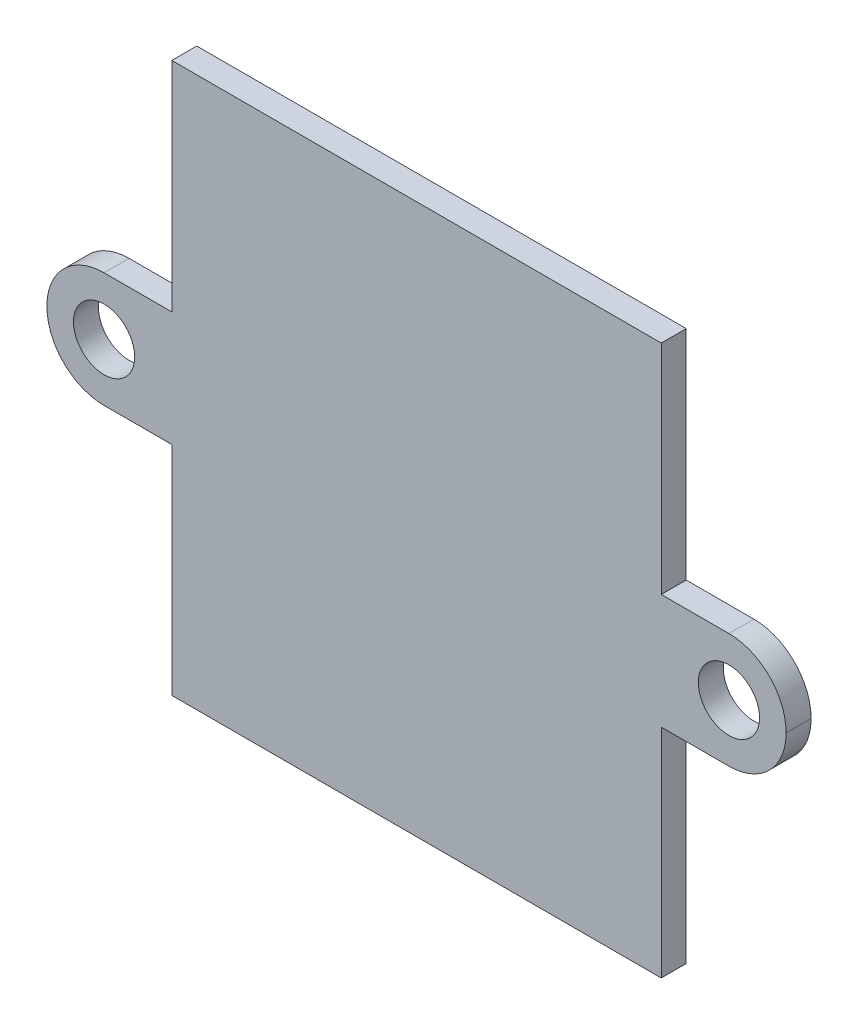
SolidWorks part; units mm, degrees
ref_plane "Płaszczyzna przednia" through (0, 0, 0) normal (0, 0, 1) x (1, 0, 0)
ref_plane "Płaszczyzna górna" through (0, 0, 0) normal (0, 1, 0) x (1, 0, 0)
ref_plane "Płaszczyzna prawa" through (0, 0, 0) normal (1, 0, 0) x (0, 0, -1)
sketch "Szkic1" plane through (0, 0, 0) normal (0, 0, 1) x (1, 0, 0)
  line L0 (12.0124, -2.9467) -> (32.4087, -2.9467) construction
  line L1 (-7.5876, 10.3733) -> (12.0124, 10.3733)
  line L2 (-7.5876, 10.3733) -> (-7.5876, 1.6533)
  line L3 (-7.5876, -11.6467) -> (12.0124, -11.6467)
  line L4 (12.0124, 10.3733) -> (12.0124, 1.6533)
  line L5 (12.0124, 1.6533) -> (32.8439, 1.6533) construction
  line L6 (17.0124, 13.5303) -> (17.0124, -14.2822) construction
  line L7 (12.0124, 1.6533) -> (14.7224, 1.6533)
  line L8 (17.0124, -0.6367) -> (17.0124, -0.6567)
  line L9 (14.7224, -2.9467) -> (12.0124, -2.9467)
  line L10 (12.0124, -2.9467) -> (12.0124, -11.6467)
  line L11 (2.2124, -11.6467) -> (2.2124, 10.3733) construction
  line L12 (-12.5876, 13.5303) -> (-12.5876, -14.2822) construction
  line L13 (-7.5876, 1.6533) -> (-28.4191, 1.6533) construction
  line L14 (-7.5876, -2.9467) -> (-27.9839, -2.9467) construction
  line L15 (-10.2976, -2.9467) -> (-7.5876, -2.9467)
  line L16 (-12.5876, -0.6367) -> (-12.5876, -0.6567)
  line L17 (-7.5876, 1.6533) -> (-10.2976, 1.6533)
  line L18 (-7.5876, -2.9467) -> (-7.5876, -11.6467)
  arc A0 (14.7224, 1.6533) -> (17.0124, -0.6367) centre (14.7224, -0.6367) cw
  arc A1 (14.7224, -2.9467) -> (17.0124, -0.6567) centre (14.7224, -0.6567) ccw
  circle A2 centre (14.7224, -0.6567) radius 1.225
  circle A3 centre (-10.2976, -0.6567) radius 1.225
  arc A4 (-10.2976, -2.9467) -> (-12.5876, -0.6567) centre (-10.2976, -0.6567) cw
  arc A5 (-10.2976, 1.6533) -> (-12.5876, -0.6367) centre (-10.2976, -0.6367) ccw
  dimension "D6" = 2.29
  dimension "D7" = 2.45
  dimension "D1" = 22.02
  dimension "D2" = 19.6
  dimension "D3" = 8.7
  dimension "D4" = 4.6
  dimension "D5" = 5
extrude "Dodanie-wyciągnięcie1" add sketch "Szkic1" along normal blind 1
ref_plane "Płaszczyzna1" through (2.2124, 0, 0) normal (1, 0, 0) x (0, 0, -1)
